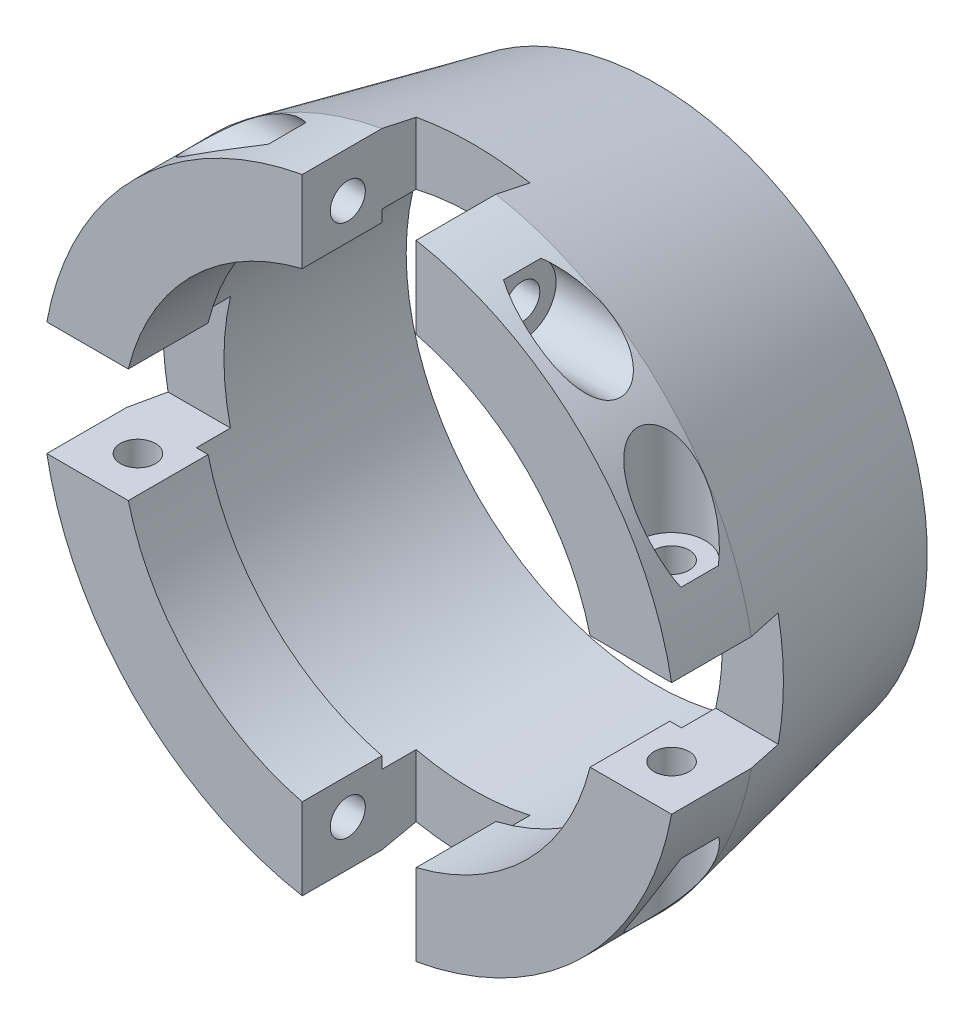
SolidWorks part; units mm, degrees
ref_plane "Front Plane" through (0, 0, 0) normal (1, 0, 0) x (0, 1, 0)
ref_plane "Top Plane" through (0, 0, 0) normal (0, 0, 1) x (0, 1, 0)
ref_plane "Right Plane" through (0, 0, 0) normal (0, 1, 0) x (-1, 0, 0)
sketch "Sketch1" plane through (0, 0, 0) normal (1, 0, 0) x (0, 1, 0)
  line L0 (0, 0) -> (27.7812, 0) construction
  line L1 (0, 0) -> (0, 33.02) construction
  line L2 (27.7812, 0) -> (27.7812, 24.13)
  line L3 (27.7812, 24.13) -> (26.5113, 24.13)
  line L4 (26.5113, 24.13) -> (26.5113, 33.02)
  line L8 (0, 33.02) -> (26.5113, 33.02) construction
  line L11 (27.7812, 0) -> (30.3213, 0)
  line L13 (35.4012, 33.02) -> (26.5113, 33.02)
  line L15 (35.4012, 33.02) -> (35.4012, 24.13)
  line L16 (35.4012, 24.13) -> (30.3213, 0)
  dimension "D1" = 27.7812
  dimension "D2" = 24.13
  dimension "D3" = 8.89
  dimension "D4" = 1.27
  dimension "D5" = 8.89
revolve "base_ring" add sketch "Sketch1" angle 360 about L1
sketch "Sketch5" plane through (0, 0, 33.02) normal (0, 0, 1) x (1, 0, 0)
  line L0 (0, 0) -> (0, 25.7395) construction
  line L1 (-6.35, 38.4395) -> (6.35, 38.4395)
  line L2 (-6.35, 38.4395) -> (-6.35, 25.7395)
  line L3 (-6.35, 25.7395) -> (6.35, 25.7395)
  line L4 (6.35, 38.4395) -> (6.35, 25.7395)
  circle A0 centre (0, 0) radius 26.5113 construction
  dimension "D1" = 12.7
  dimension "D2" = 12.7
extrude "Cut-Extrude2" cut sketch "Sketch5" against normal blind 12.7 and the other way through all
ref_plane "Plane1" through (35.4012, 0, 0) normal (1, 0, 0) x (0, 0, -1)
sketch "Sketch7" plane through (35.4012, 0, 0) normal (1, 0, 0) x (0, 0, -1)
  line L6 (-27.94, 29.7471) -> (-27.94, 34.8271) construction
  line L7 (-24.13, 34.8271) -> (-33.02, 34.8271) construction
  line L9 (-24.13, 34.8271) -> (-24.13, -35.4012) construction
  point P0 (-27.94, 29.7471)
  dimension "D1" = 3.81
  dimension "D2" = 5.08
hole_wizard "pulley_bolt_hole" positions "Sketch7" profile "Sketch8" counterbore size "#5" standard "ANSI Inch"
sketch "Sketch8" plane through (35.4012, 29.7471, 27.94) normal (0, 1, 0) x (0, 0, -1)
  line L0 (0, 0) -> (0, 39.2752)
  line L1 (0, 39.2752) -> (1.9558, 38.1)
  line L2 (1.9558, 38.1) -> (1.9558, 22.3012)
  line L3 (1.9558, 22.3012) -> (3.7706, 22.3012)
  line L4 (3.7706, 22.3012) -> (3.7706, 0)
  line L5 (3.7706, 0) -> (0, 0)
  line L10 (0, 39.2752) -> (-1.9558, 38.1) construction
  line L11 (0, -6.35) -> (0, 107.95) construction
  dimension "Hole Dia." = 3.9116
  dimension "Hole Depth" = 38.1
  dimension "C'Bore Dia." = 7.5413
  dimension "C'Bore Depth" = 22.3012
  dimension "Drill Angle" = 118
mirror "bolthole_mirror" about plane through (0, 0, 0) normal (1, 0, 0) of "pulley_bolt_hole"
pattern_circular "CirPattern1" count 4 over 360 about axis through (0, 0, 0) along (0, 0, 1) of "Cut-Extrude2", "pulley_bolt_hole", "bolthole_mirror"
